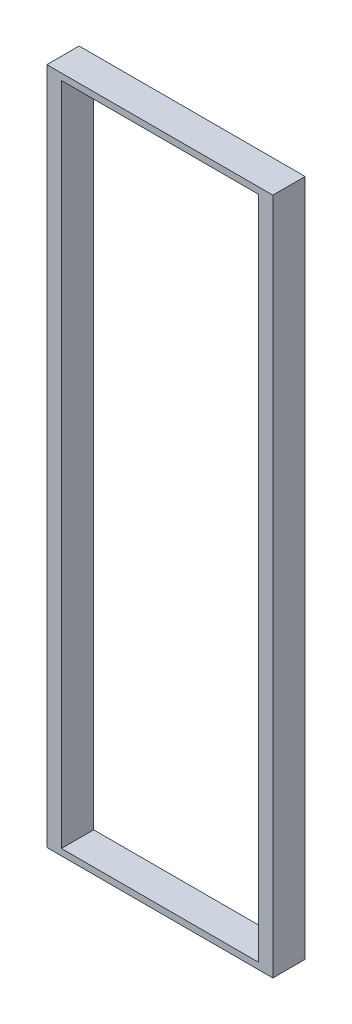
SolidWorks part; units mm, degrees
ref_plane "Спереди" through (0, 0, 0) normal (0, 0, 1) x (1, 0, 0)
ref_plane "Сверху" through (0, 0, 0) normal (0, 1, 0) x (1, 0, 0)
ref_plane "Справа" through (0, 0, 0) normal (1, 0, 0) x (0, 0, -1)
sketch "Эскиз1" plane through (0, 0, 0) normal (0, 0, 1) x (1, 0, 0)
  line L1 (0, 0) -> (700, 0)
  line L2 (0, 0) -> (0, 2100)
  line L3 (0, 2100) -> (700, 2100)
  line L4 (700, 0) -> (700, 2100)
  line L5 (45, 2080) -> (655, 2080)
  line L6 (45, 2080) -> (45, 20)
  line L7 (45, 20) -> (655, 20)
  line L8 (655, 2080) -> (655, 20)
  dimension "D1" = 700
  dimension "D2" = 2100
  dimension "D3" = 20
  dimension "D4" = 20
  dimension "D5" = 45
  dimension "D6" = 45
extrude "Бобышка-Вытянуть1" add sketch "Эскиз1" along normal blind 100
